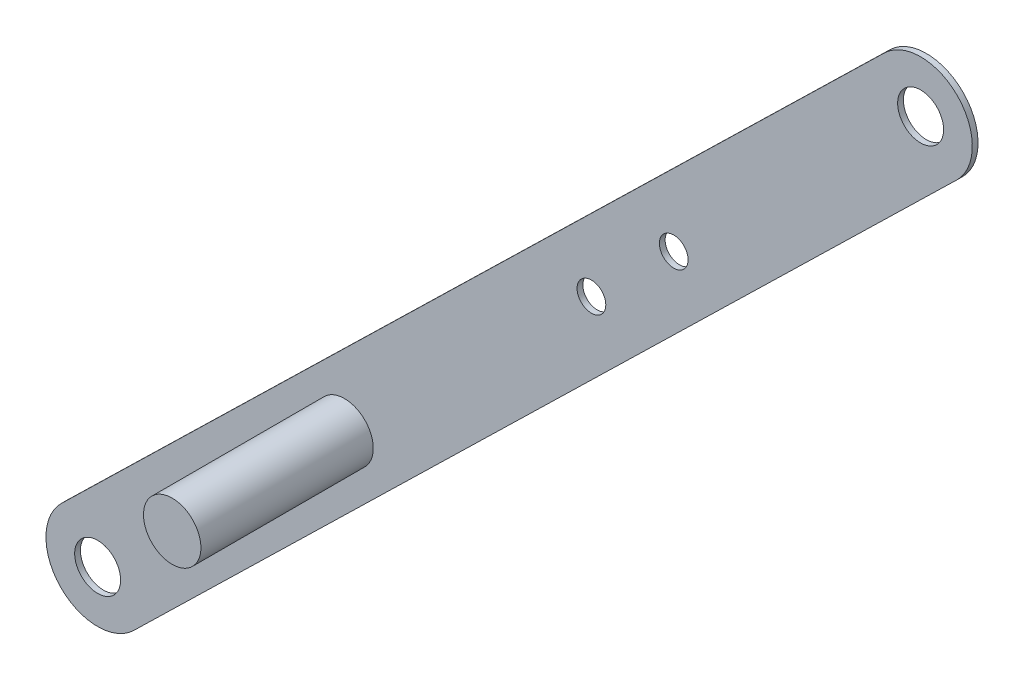
SolidWorks part; units mm, degrees
ref_plane "Front Plane" through (0, 0, 0) normal (0, 0, 1) x (1, 0, 0)
ref_plane "Top Plane" through (0, 0, 0) normal (0, 1, 0) x (1, 0, 0)
ref_plane "Right Plane" through (0, 0, 0) normal (1, 0, 0) x (0, 0, -1)
sketch "Sketch1" plane through (0, 0, 0) normal (0, 0, 1) x (1, 0, 0)
  line L0 (0, 0) -> (-143.2709, -139.5473) construction
  line L1 (6.2796, -6.4472) -> (-136.9913, -145.9945)
  line L2 (-6.2796, 6.4472) -> (-149.5505, -133.1001)
  arc A0 (6.2796, -6.4472) -> (-6.2796, 6.4472) centre (0, 0) ccw
  arc A1 (-149.5505, -133.1001) -> (-136.9913, -145.9945) centre (-143.2709, -139.5473) ccw
  circle A2 centre (0, 0) radius 4
  circle A3 centre (-143.2709, -139.5473) radius 4
  circle A4 centre (-42.9813, -41.8642) radius 2.5
  circle A5 centre (-57.3084, -55.8189) radius 2.5
  point P3 (-71.6355, -69.7736)
  dimension "D1" = 8
  dimension "D2" = 8
  dimension "D3" = 9
  dimension "D5" = 5
  dimension "D6" = 5
  dimension "D4" = 200
  dimension "D7" = 20
  dimension "D8" = 60
extrude "Boss-Extrude1" add sketch "Sketch1" along normal blind 1
sketch "Sketch2" plane through (0, 0, 1) normal (0, 0, 1) x (1, 0, 0)
  line L0 (-136.9913, -145.9945) -> (6.2796, -6.4472) construction
  circle A0 centre (-100.2896, -97.6831) radius 5
  circle A1 centre (-143.2709, -139.5473) radius 4 construction
  point P4 (0, 0)
  point P5 (0, 0)
  dimension "D1" = 10
  dimension "D2" = 60
  dimension "D3" = 9
extrude "Boss-Extrude2" add sketch "Sketch2" along normal blind 30
